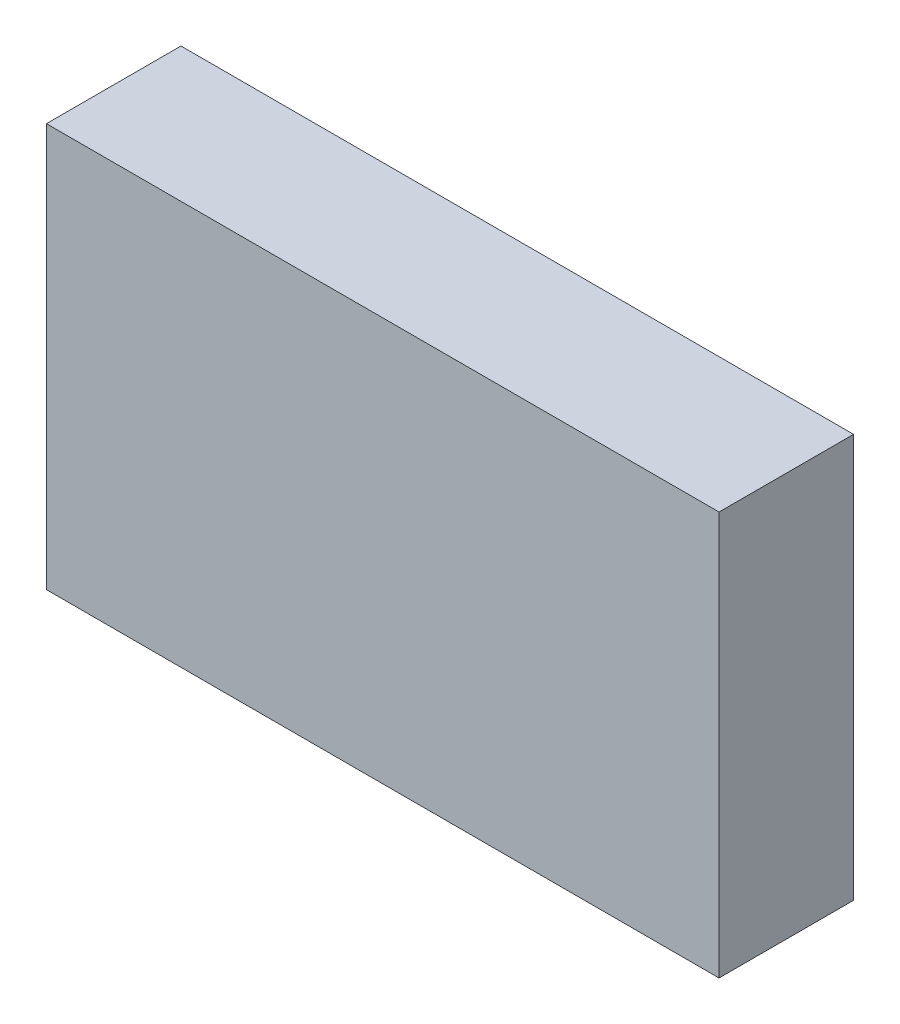
SolidWorks part; units mm, degrees
ref_plane "Front Plane" through (0, 0, 0) normal (0, 0, 1) x (1, 0, 0)
ref_plane "Top Plane" through (0, 0, 0) normal (0, 1, 0) x (1, 0, 0)
ref_plane "Right Plane" through (0, 0, 0) normal (1, 0, 0) x (0, 0, -1)
sketch "Sketch1" plane through (0, 0, 0) normal (0, 0, 1) x (1, 0, 0)
  line L1 (0, 0) -> (100, 0)
  line L2 (0, 0) -> (0, 60)
  line L3 (0, 60) -> (100, 60)
  line L4 (100, 0) -> (100, 60)
extrude "SimpleBlock" add sketch "Sketch1" along normal blind 20
